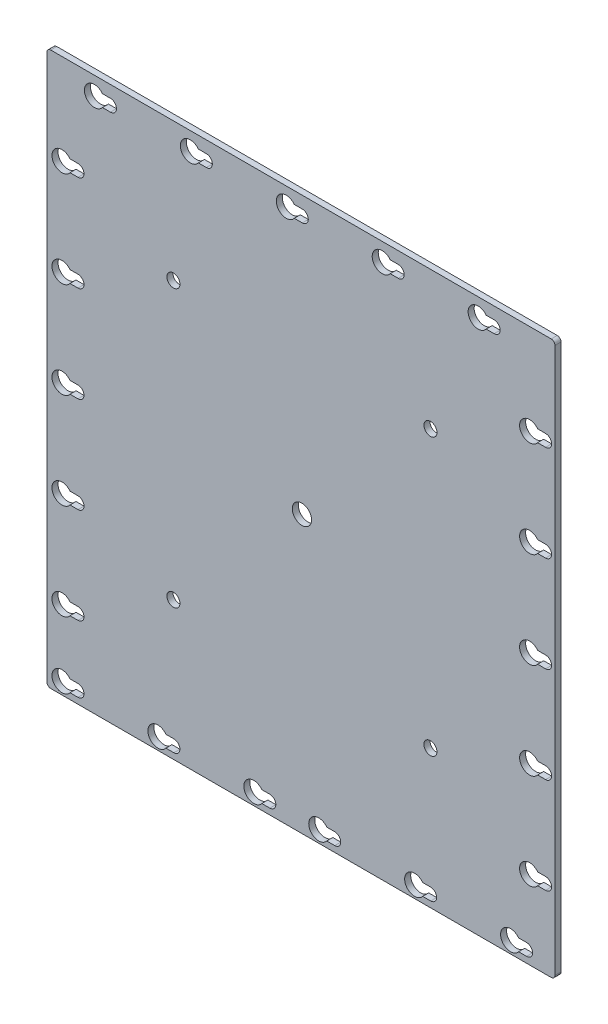
SolidWorks part; units mm, degrees
material "6061 Alloy"
ref_plane "Front Plane" through (0, 0, 0) normal (0, 0, 1) x (1, 0, 0)
ref_plane "Top Plane" through (0, 0, 0) normal (0, 1, 0) x (1, 0, 0)
ref_plane "Right Plane" through (0, 0, 0) normal (1, 0, 0) x (0, 0, -1)
sketch "Sketch1" plane through (0, 0, 0) normal (0, 0, 1) x (1, 0, 0)
  line L0 (0, 0) -> (0, -146.4313)
  line L3 (0, -146.4313) -> (135.0197, -146.4313)
  line L5 (0, 0) -> (135.0197, 0)
  line L6 (135.0197, -146.4313) -> (135.0197, 0)
  line L7 (67.5099, 0) -> (67.5099, -146.4313) construction
  line L8 (16.8049, -3.175) -> (14.6893, -3.175)
  line L9 (16.8049, -6.35) -> (14.6893, -6.35)
  line L10 (76.2, -144.8438) -> (74.0844, -144.8438)
  line L11 (76.2, -141.6688) -> (74.0844, -141.6688)
  line L12 (101.6, -141.6688) -> (99.4844, -141.6688)
  line L13 (101.6, -144.8438) -> (99.4844, -144.8438)
  line L14 (42.2049, -3.175) -> (40.0893, -3.175)
  line L15 (42.2049, -6.35) -> (40.0893, -6.35)
  line L16 (67.6049, -3.175) -> (65.4893, -3.175)
  line L17 (67.6049, -6.35) -> (65.4893, -6.35)
  line L18 (93.0049, -3.175) -> (90.8893, -3.175)
  line L19 (93.0049, -6.35) -> (90.8893, -6.35)
  line L20 (118.4049, -3.175) -> (116.2893, -3.175)
  line L21 (118.4049, -6.35) -> (116.2893, -6.35)
  line L22 (127, -141.6688) -> (124.8844, -141.6688)
  line L23 (127, -144.8438) -> (124.8844, -144.8438)
  line L25 (8.2099, -98.6156) -> (6.0942, -98.6156)
  line L26 (8.2099, -101.7906) -> (6.0942, -101.7906)
  line L27 (8.2099, -73.2156) -> (6.0942, -73.2156)
  line L28 (8.2099, -76.3906) -> (6.0942, -76.3906)
  line L29 (8.2099, -47.8156) -> (6.0942, -47.8156)
  line L30 (8.2099, -50.9906) -> (6.0942, -50.9906)
  line L31 (8.2099, -22.4156) -> (6.0942, -22.4156)
  line L32 (8.2099, -25.5906) -> (6.0942, -25.5906)
  line L33 (132.0349, -124.0156) -> (129.9192, -124.0156)
  line L34 (132.0349, -127.1906) -> (129.9192, -127.1906)
  line L35 (132.0349, -98.6156) -> (129.9192, -98.6156)
  line L36 (132.0349, -101.7906) -> (129.9192, -101.7906)
  line L37 (132.0349, -73.2156) -> (129.9192, -73.2156)
  line L38 (8.2099, -124.0156) -> (6.0942, -124.0156)
  line L39 (8.2099, -127.1906) -> (6.0942, -127.1906)
  line L40 (132.0349, -76.3906) -> (129.9192, -76.3906)
  line L41 (132.0349, -47.8156) -> (129.9192, -47.8156)
  line L42 (8.2099, -141.6688) -> (6.0943, -141.6688)
  line L43 (8.2099, -144.8438) -> (6.0943, -144.8438)
  line L44 (33.6099, -141.6688) -> (31.4943, -141.6688)
  line L45 (33.6099, -144.8438) -> (31.4943, -144.8438)
  line L46 (59.0099, -141.6688) -> (56.8943, -141.6688)
  line L47 (59.0099, -144.8438) -> (56.8943, -144.8438)
  line L48 (132.0349, -50.9906) -> (129.9192, -50.9906)
  line L49 (132.0349, -22.4156) -> (129.9192, -22.4156)
  line L50 (132.0349, -25.5906) -> (129.9192, -25.5906)
  line L54 (0, 0) -> (0, -146.4313)
  line L55 (135.0197, -146.4313) -> (135.0197, 0)
  line L56 (0, -146.4313) -> (135.0197, -146.4313)
  circle A41 centre (8.2099, -125.6031) radius 1.5875
  circle A42 centre (8.2099, -143.2563) radius 1.5875
  circle A49 centre (33.6099, -143.2563) radius 1.5875
  circle A50 centre (59.0099, -143.2563) radius 1.5875
  circle A69 centre (93.0049, -4.7625) radius 1.5875
  circle A70 centre (67.6049, -4.7625) radius 1.5875
  circle A71 centre (42.2049, -4.7625) radius 1.5875
  circle A73 centre (118.4049, -4.7625) radius 1.5875
  circle A74 centre (16.8049, -4.7625) radius 1.5875
  circle A81 centre (12.5674, -4.7625) radius 2.65
  circle A85 centre (37.9674, -4.7625) radius 2.65
  circle A86 centre (63.3674, -4.7625) radius 2.65
  circle A87 centre (88.7674, -4.7625) radius 2.65
  circle A88 centre (114.1674, -4.7625) radius 2.65
  circle A97 centre (3.9724, -125.6031) radius 2.65
  circle A99 centre (3.9724, -143.2563) radius 2.65
  circle A100 centre (29.3724, -143.2563) radius 2.65
  circle A101 centre (54.7724, -143.2563) radius 2.65
  circle A105 centre (67.5099, -73.2156) radius 2.5527
  circle A106 centre (84.4099, -143.2563) radius 1.5875 [skipped]
  circle A107 centre (109.8099, -143.2563) radius 1.5875 [skipped]
  circle A108 centre (76.2, -143.2563) radius 1.5875
  circle A109 centre (71.9625, -143.2563) radius 2.65
  circle A110 centre (97.3625, -143.2563) radius 2.65
  circle A111 centre (101.6, -143.2563) radius 1.5875
  circle A112 centre (122.7625, -143.2563) radius 2.65
  circle A113 centre (127, -143.2563) radius 1.5875
  circle A114 centre (3.9724, -100.2031) radius 2.65
  circle A115 centre (8.2099, -100.2031) radius 1.5875
  circle A116 centre (3.9724, -74.8031) radius 2.65
  circle A117 centre (8.2099, -74.8031) radius 1.5875
  circle A118 centre (3.9724, -49.4031) radius 2.65
  circle A119 centre (8.2099, -49.4031) radius 1.5875
  circle A120 centre (3.9724, -24.0031) radius 2.65
  circle A121 centre (8.2099, -24.0031) radius 1.5875
  circle A122 centre (132.0349, -125.6031) radius 1.5875
  circle A123 centre (127.7974, -125.6031) radius 2.65
  circle A124 centre (127.7974, -100.2031) radius 2.65
  circle A125 centre (132.0349, -100.2031) radius 1.5875
  circle A126 centre (127.7974, -74.8031) radius 2.65
  circle A127 centre (132.0349, -74.8031) radius 1.5875
  circle A128 centre (127.7974, -49.4031) radius 2.65
  circle A129 centre (132.0349, -49.4031) radius 1.5875
  circle A130 centre (127.7974, -24.0031) radius 2.65
  circle A131 centre (132.0349, -24.0031) radius 1.5875
  dimension "D8" = 3.175
  dimension "D21" = 5.3
  dimension "D31" = 5.1054
  dimension "D33" = 5.3
  dimension "D9" = 5.3
  dimension "D1" = 135.0197
  dimension "D2" = 146.4313
  dimension "D6" = 8.2099
  dimension "D7" = 3.175
  dimension "D10" = 25.4
  dimension "D23" = 25.4
  dimension "D27" = 25.4
  dimension "D28" = 0
  dimension "D29" = 0
  dimension "D30" = 73.2156
  dimension "D13" = 25.4
  dimension "D5" = 17.1901
  dimension "D15" = 25.4
  dimension "D19" = 25.4
  dimension "D25" = 25.4
  dimension "D12" = 4.7625
  dimension "D17" = 16.8049
  dimension "D20" = 132.0349
  dimension "D4" = 24.0031
  dimension "D32" = 24.0031
  dimension "D34" = 8.2099
  dimension "D14" = 5
  dimension "D16" = 5
  dimension "D22" = 5
  dimension "D26" = 3
  dimension "D11" = 3
  dimension "D18" = 5
  dimension "D24" = 5
extrude "Boss-Extrude1" add sketch "Sketch1" along normal blind 1.6
sketch "Sketch3" plane through (0, 0, 1.6) normal (0, 0, 1) x (1, 0, 0)
  line L0 (134.5197, 0) -> (134.5197, -146.4313)
  line L1 (0, 0) -> (135.0197, 0) construction
  line L2 (0, -146.4313) -> (135.0197, -146.4313) construction
  line L3 (135.0197, -146.4313) -> (135.0197, 0) construction
  line L4 (134.5197, 0) -> (135.0197, 0)
  line L5 (135.0197, 0) -> (135.0197, -146.4313)
  line L6 (135.0197, -146.4313) -> (134.5197, -146.4313)
  dimension "D1" = 0.5
extrude "Cut-Extrude1" cut sketch "Sketch3" against normal up to surface (1.6 mm away) up to face at (65.751, -4.7625, 0)
fillet "Fillet1" radius 1 4 edges at (0, -146.4313, 0.8) (0, 0, 0.8) (134.5197, -146.4313, 0.8) (134.5197, 0, 0.8)
sketch "Sketch4" plane through (0, 0, 1.6) normal (0, 0, 1) x (1, 0, 0)
  line L0 (134.5197, -1) -> (0, -1) construction
  line L1 (33.4799, -36.6078) -> (101.5398, -36.6078) construction
  line L2 (33.4799, -36.6078) -> (33.4799, -109.8235) construction
  line L3 (33.4799, -109.8235) -> (101.5398, -109.8235) construction
  line L4 (101.5398, -36.6078) -> (101.5398, -109.8235) construction
  line L5 (33.4799, -36.6078) -> (101.5398, -109.8235) construction
  line L6 (33.4799, -109.8235) -> (101.5398, -36.6078) construction
  line L7 (1, 0) -> (1, -146.4313) construction
  line L8 (0, -1) -> (133.9197, -1) construction
  circle A3 centre (33.4799, -36.6078) radius 1.725
  circle A4 centre (101.5398, -36.6078) radius 1.725
  circle A5 centre (101.5398, -109.8235) radius 1.725
  circle A6 centre (33.4799, -109.8235) radius 1.725
  point P4 (67.5099, -73.2156)
  dimension "D2" = 146.4313
  dimension "D3" = 3.45
  dimension "D1" = 134.5197
  dimension "D4" = 33.4799
  dimension "D5" = 36.6078
  dimension "D6" = 133.9197
  dimension "D7" = 0.6
extrude "Cut-Extrude2" cut sketch "Sketch4" against normal through all both
equation "\"D29@Sketch1\"= \"D28@Sketch1\""
equation "\"D30@Sketch1\"=\"D2@Sketch1\"/2"
equation "\"D13@Sketch1\"=\"D23@Sketch1\""
equation "\"Hole_Offset\"= 1.2083"
equation "\"D6@Sketch1\"=8.209+0.0009"
equation "\"D15@Sketch1\"=\"D27@Sketch1\""
equation "\"D25@Sketch1\"=\"D19@Sketch1\""
equation "\"D17@Sketch1\"=16.8046+0.0003"
equation "\"D2@Sketch1\"=146.4315890mm-0.0003"
equation "\"D4@Sketch4\"=\"D6@Sketch4\"/4"
equation "\"D5@Sketch4\"=\"D2@Sketch4\"/4"
